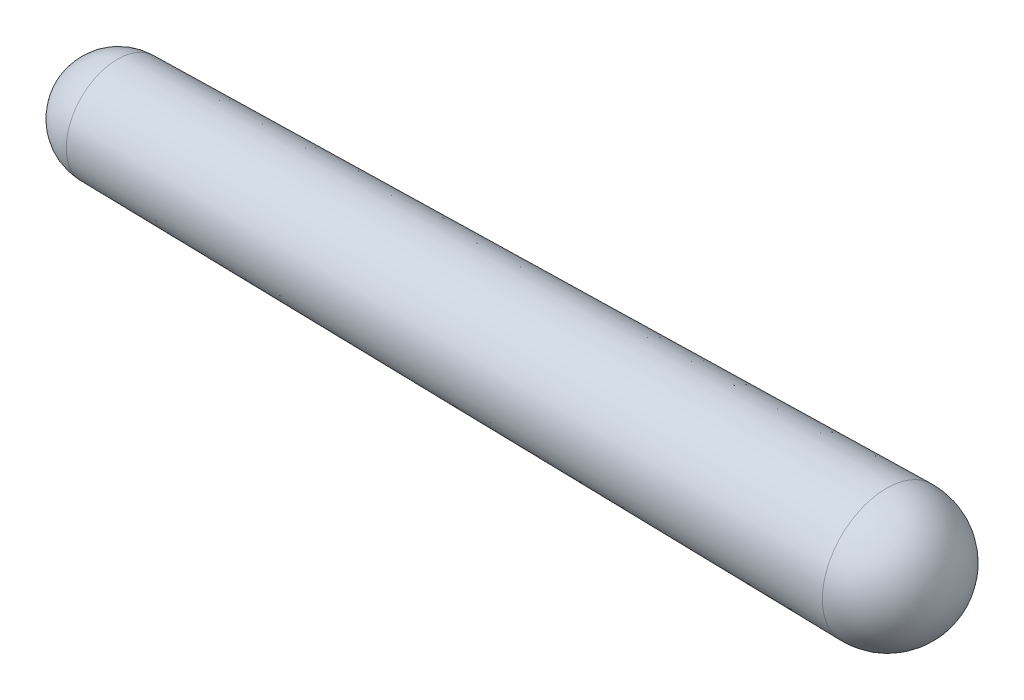
SolidWorks part; units mm, degrees
material "Melamine resin"
ref_plane "Front Plane" through (0, 0, 0) normal (0, 0, 1) x (1, 0, 0)
ref_plane "Top Plane" through (0, 0, 0) normal (0, 1, 0) x (1, 0, 0)
ref_plane "Right Plane" through (0, 0, 0) normal (1, 0, 0) x (0, 0, -1)
sketch "Sketch1" plane through (0, 0, 0) normal (0, 1, 0) x (1, 0, 0)
  line L0 (-30.0333, 1.9997) -> (-0.0417, 2.4997)
  line L1 (-32, 0) -> (2.5, 0)
  arc A0 (2.5, 0) -> (-0.0417, 2.4997) centre (0, 0) ccw
  arc A1 (-30.0333, 1.9997) -> (-32, 0) centre (-30, 0) ccw
  dimension "D2" = 4
  dimension "D3" = 5
  dimension "D1" = 30
revolve "Revolve1" add sketch "Sketch1" angle 360 about L1
